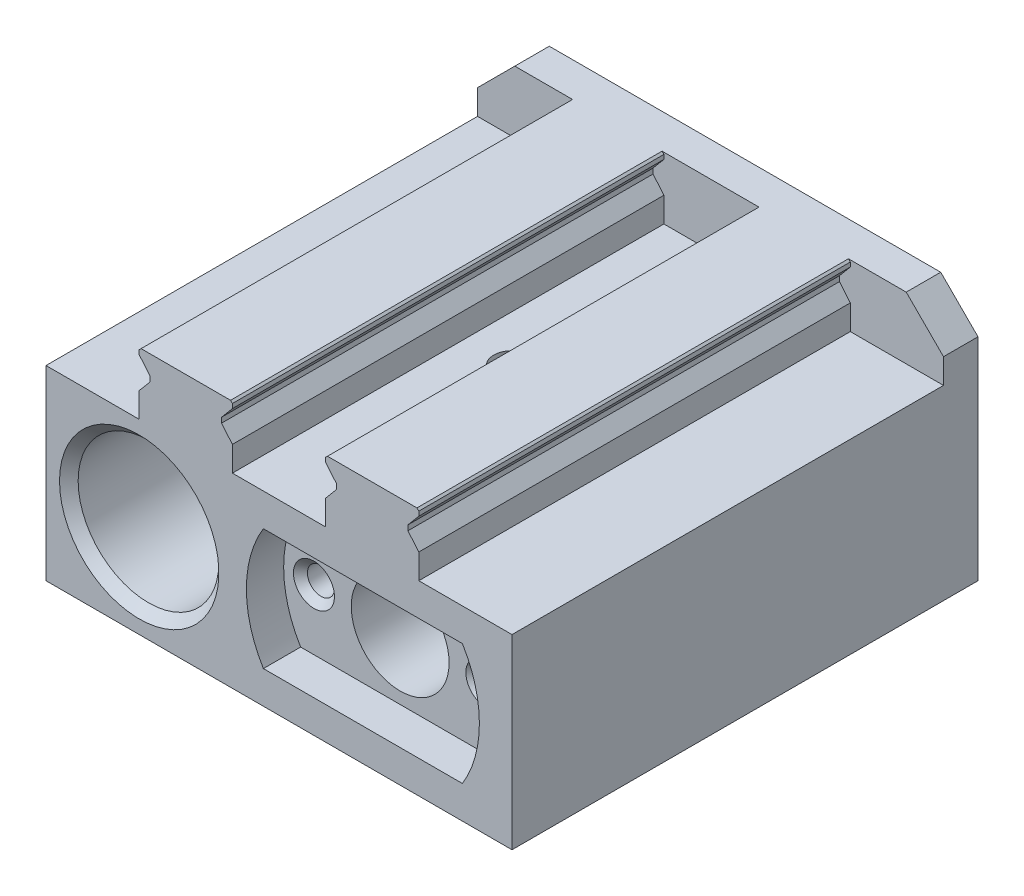
SolidWorks part; units mm, degrees
material "PET"
ref_plane "Přední rovina" through (0, 0, 0) normal (0, 0, 1) x (1, 0, 0)
ref_plane "Horní rovina" through (0, 0, 0) normal (0, 1, 0) x (1, 0, 0)
ref_plane "Pravá rovina" through (0, 0, 0) normal (1, 0, 0) x (0, 0, -1)
sketch "Skica4" plane through (0, 0, 0) normal (0, 1, 0) x (1, 0, 0)
  line L1 (-25, -25) -> (25, -25)
  line L2 (-25, -25) -> (-25, 25)
  line L3 (-25, 25) -> (25, 25)
  line L4 (25, -25) -> (25, 25)
  line L5 (-25, -25) -> (25, 25) construction
  line L6 (-25, 25) -> (25, -25) construction
  point P0 (0, 0)
  dimension "D1" = 50
  dimension "D2" = 50
extrude "Přidat vysunutím2" add sketch "Skica4" along normal blind 20
sketch "Skica5" plane through (0, 0, 25) normal (0, 0, 1) x (1, 0, 0)
  line L0 (-25, 10) -> (25, 10) construction
  line L1 (-25, 20) -> (-25, 0) construction
  line L2 (25, 20) -> (25, 0) construction
  line L3 (-1.6771, 16.5) -> (19.6771, 16.5)
  line L4 (-1.6771, 3.5) -> (19.6771, 3.5)
  circle A0 centre (9, 10) radius 4 construction
  arc A1 (-1.6771, 16.5) -> (-1.6771, 3.5) centre (9, 10) ccw
  arc A2 (19.6771, 3.5) -> (19.6771, 16.5) centre (9, 10) ccw
  dimension "D1" = 8
  dimension "D2" = 25
  dimension "D3" = 13
  dimension "D4" = 16
extrude "Odebrat vysunutím3" cut sketch "Skica5" against normal blind 3.5
sketch "Skica6" plane through (0, 0, 21.5) normal (0, 0, 1) x (1, 0, 0)
  line L0 (-3.5, 10) -> (21.5, 10) construction
  line L1 (9, 16.5) -> (9, 3.5) construction
  line L2 (19.6771, 16.5) -> (-1.6771, 16.5) construction
  line L3 (-1.6771, 3.5) -> (19.6771, 3.5) construction
  arc A0 (-1.6771, 16.5) -> (-1.6771, 3.5) centre (9, 10) ccw construction
  arc A1 (19.6771, 3.5) -> (19.6771, 16.5) centre (9, 10) ccw construction
  circle A2 centre (-0.25, 10) radius 1.45
  circle A3 centre (18.25, 10) radius 1.45
  dimension "D1" = 2.9
  dimension "D2" = 2.9
  dimension "D3" = 18.5
extrude "Odebrat vysunutím4" cut sketch "Skica6" against normal blind 14
mirror "Zrcadlit1" about plane through (0, 0, 0) normal (0, 0, 1) of "Odebrat vysunutím4", "Odebrat vysunutím3"
sketch "Skica7" plane through (0, 0, 21.5) normal (0, 0, 1) x (1, 0, 0)
  line L0 (-3.5, 10) -> (21.5, 10) construction
  arc A0 (-1.6771, 16.5) -> (-1.6771, 3.5) centre (9, 10) ccw construction
  arc A1 (19.6771, 3.5) -> (19.6771, 16.5) centre (9, 10) ccw construction
  circle A2 centre (9, 10) radius 5.25
  dimension "D1" = 10.5
extrude "Odebrat vysunutím5" cut sketch "Skica7" against normal through all
sketch "Skica8" plane through (0, 0, 25) normal (0, 0, 1) x (1, 0, 0)
  line L0 (-25, 10) -> (25, 10) construction
  line L1 (-25, 20) -> (-25, 0) construction
  line L2 (25, 20) -> (25, 0) construction
  circle A0 centre (-15, 10) radius 7.55
  dimension "D1" = 15.1
  dimension "D2" = 10
extrude "Odebrat vysunutím6" cut sketch "Skica8" against normal through all
sketch "Skica11" plane through (0, 0, -25) normal (0, 0, -1) x (-1, 0, 0)
  line L0 (-15, 20) -> (-15, 22.67)
  line L1 (-25, 20) -> (25, 20) construction
  line L2 (-15, 22.67) -> (-13.8337, 24.06)
  line L3 (-13.8337, 24.06) -> (-13.8337, 24.61)
  line L4 (-13.8337, 24.61) -> (-15, 26)
  line L5 (-15, 26) -> (-15, 26.47)
  line L6 (-14.8, 26.67) -> (-5.2, 26.67)
  line L7 (-15, 20) -> (-5, 20)
  line L8 (-10, 20) -> (-10, 26.67) construction
  line L9 (-5, 26) -> (-5, 26.47)
  line L10 (-6.1663, 24.61) -> (-5, 26)
  line L11 (-6.1663, 24.06) -> (-6.1663, 24.61)
  line L12 (-5, 22.67) -> (-6.1663, 24.06)
  line L13 (-5, 20) -> (-5, 22.67)
  line L14 (-25, 20) -> (-25, 0) construction
  line L15 (0, 0) -> (0, 38.4714) construction
  line L16 (-25, 0) -> (25, 0) construction
  line L17 (15, 20) -> (15, 22.67)
  line L18 (15, 22.67) -> (13.8337, 24.06)
  line L19 (13.8337, 24.06) -> (13.8337, 24.61)
  line L20 (13.8337, 24.61) -> (15, 26)
  line L21 (15, 26) -> (15, 26.47)
  line L22 (14.8, 26.67) -> (5.2, 26.67)
  line L23 (5, 26) -> (5, 26.47)
  line L24 (6.1663, 24.61) -> (5, 26)
  line L25 (6.1663, 24.06) -> (6.1663, 24.61)
  line L26 (5, 22.67) -> (6.1663, 24.06)
  line L27 (5, 20) -> (5, 22.67)
  line L28 (15, 20) -> (5, 20)
  line L30 (-15, 26.47) -> (-14.8, 26.67)
  line L31 (-5.2, 26.67) -> (-5, 26.47)
  line L32 (5.2, 26.67) -> (5, 26.47)
  line L33 (15, 26.47) -> (14.8, 26.67)
  point P8 (-15, 26.67)
  point P14 (-5, 26.67)
  point P27 (15, 26.67)
  point P28 (5, 26.67)
  dimension "D1" = 10
  dimension "D2" = 6.67
  dimension "D3" = 2.67
  dimension "D4" = 3.33
  dimension "D5" = 0.55
  dimension "D6" = 50
  dimension "D7" = 50
  dimension "D8" = 15
extrude "Přidat vysunutím4" add sketch "Skica11" against normal up to surface (50 mm away) up to face at (-7.45, 10, 25)
sketch "Skica12" plane through (0, 20, 0) normal (0, 1, 0) x (1, 0, 0)
  circle A0 centre (0, 0) radius 1.95
  dimension "D1" = 3.9
extrude "Odebrat vysunutím7" cut sketch "Skica12" against normal through all
sketch "Skica13" plane through (0, 0, 0) normal (0, -1, 0) x (1, 0, 0)
  circle A0 centre (0, 0) radius 4
  dimension "D1" = 8
extrude "Odebrat vysunutím8" cut sketch "Skica13" against normal blind 6
sketch "Skica14" plane through (25, 0, 0) normal (1, 0, 0) x (0, 0, -1)
  line L0 (-25, 20) -> (25, 20) construction
  line L1 (25, 26.67) -> (21.3, 26.67)
  line L2 (25, 26.67) -> (25, 20)
  line L3 (25, 20) -> (21.3, 20)
  line L4 (21.3, 26.67) -> (21.3, 20)
  line L5 (25, 26.67) -> (21.3, 20) construction
  line L6 (25, 20) -> (21.3, 26.67) construction
  point P4 (23.15, 23.335)
  dimension "D1" = 3.7
extrude "Přidat vysunutím5" add sketch "Skica14" against normal up to surface (50 mm away) up to face at (-25, 10, 0)
chamfer "Zkosení1" distance 1 angle 45 1 edges at (-7.45, 10, 25)
sketch "Skica16" plane through (0, 0, -21.5) normal (0, 0, -1) x (-1, 0, 0)
  line L2 (1.6771, 16.5) -> (-19.6771, 16.5)
  line L3 (-19.6771, 3.5) -> (1.6771, 3.5)
  line L4 (1.6771, 16.5) -> (-19.6771, 16.5)
  line L5 (-19.6771, 3.5) -> (1.6771, 3.5)
  arc A2 (1.6771, 3.5) -> (1.6771, 16.5) centre (-9, 10) ccw
  arc A3 (-19.6771, 16.5) -> (-19.6771, 3.5) centre (-9, 10) ccw
  arc A4 (1.6771, 3.5) -> (1.6771, 16.5) centre (-9, 10) ccw
  arc A5 (-19.6771, 16.5) -> (-19.6771, 3.5) centre (-9, 10) ccw
  dimension "D1" = 0
extrude "Odebrat vysunutím9" cut sketch "Skica16" against normal blind 2
sketch "Skica17" plane through (0, 0, 21.5) normal (0, 0, 1) x (1, 0, 0)
  line L2 (-1.6771, 3.5) -> (19.6771, 3.5)
  line L3 (19.6771, 16.5) -> (-1.6771, 16.5)
  line L4 (-1.6771, 3.5) -> (19.6771, 3.5)
  line L5 (19.6771, 16.5) -> (-1.6771, 16.5)
  arc A2 (-1.6771, 16.5) -> (-1.6771, 3.5) centre (9, 10) ccw
  arc A3 (19.6771, 3.5) -> (19.6771, 16.5) centre (9, 10) ccw
  arc A4 (-1.6771, 16.5) -> (-1.6771, 3.5) centre (9, 10) ccw
  arc A5 (19.6771, 3.5) -> (19.6771, 16.5) centre (9, 10) ccw
  dimension "D1" = 0
extrude "Odebrat vysunutím10" cut sketch "Skica17" against normal blind 0.5
chamfer "Zkosení2" distance 0.75 angle 45 4 edges at (16.8, 10, -19.5) (-1.7, 10, -19.5) (19.7, 10, 21) (1.2, 10, 21)
chamfer "Zkosení3" distance 4 angle 45 2 edges at (25, 26.67, -23.15) (-25, 26.67, -23.15)
